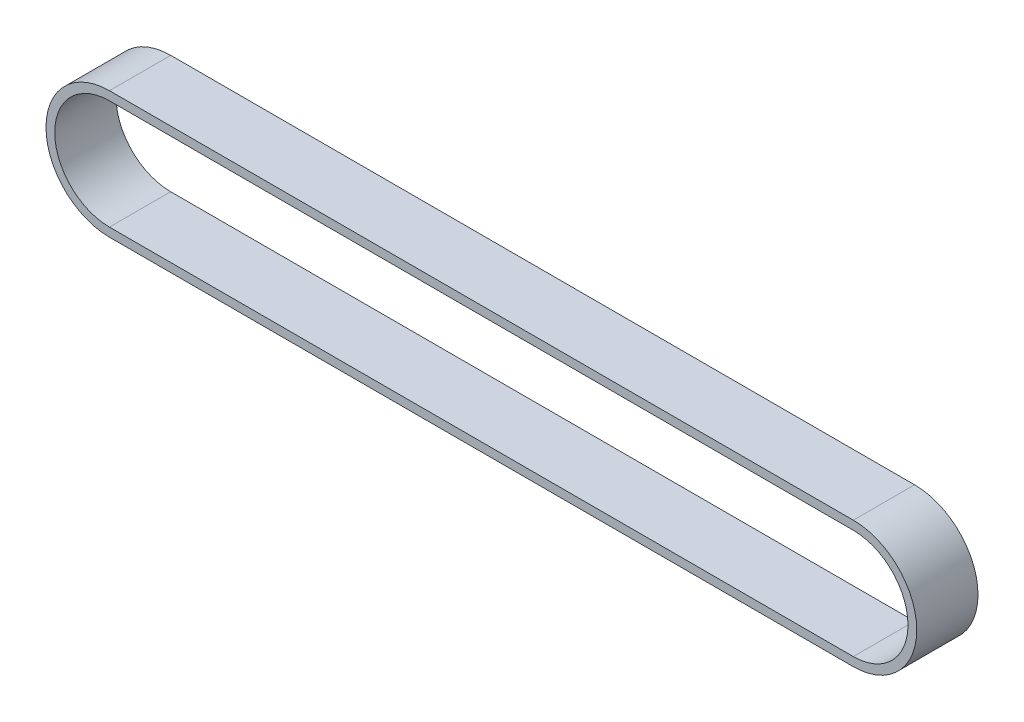
SolidWorks part; units mm, degrees
ref_plane "Front Plane" through (0, 0, 0) normal (0, 0, 1) x (1, 0, 0)
ref_plane "Top Plane" through (0, 0, 0) normal (0, 1, 0) x (1, 0, 0)
ref_plane "Right Plane" through (0, 0, 0) normal (1, 0, 0) x (0, 0, -1)
sketch "Sketch1" plane through (0, 0, 0) normal (0, 0, 1) x (1, 0, 0)
  line L0 (-20.1444, 0) -> (15.5592, 0) construction
  line L1 (0, 30.6948) -> (0, -22.989) construction
  line L2 (-85, 12.5) -> (85, 12.5)
  line L3 (-85, -12.5) -> (85, -12.5)
  line L4 (-85, 14.5) -> (85, 14.5)
  line L5 (-85, -14.5) -> (85, -14.5)
  arc A0 (-85, 12.5) -> (-85, -12.5) centre (-85, 0) ccw
  arc A1 (85, 12.5) -> (85, -12.5) centre (85, 0) cw
  arc A2 (85, 14.5) -> (85, -14.5) centre (85, 0) cw
  arc A3 (-85, 14.5) -> (-85, -14.5) centre (-85, 0) ccw
  dimension "D1" = 25
  dimension "D2" = 170
  dimension "D3" = 2
extrude "Boss-Extrude1" add sketch "Sketch1" along normal mid plane 14
